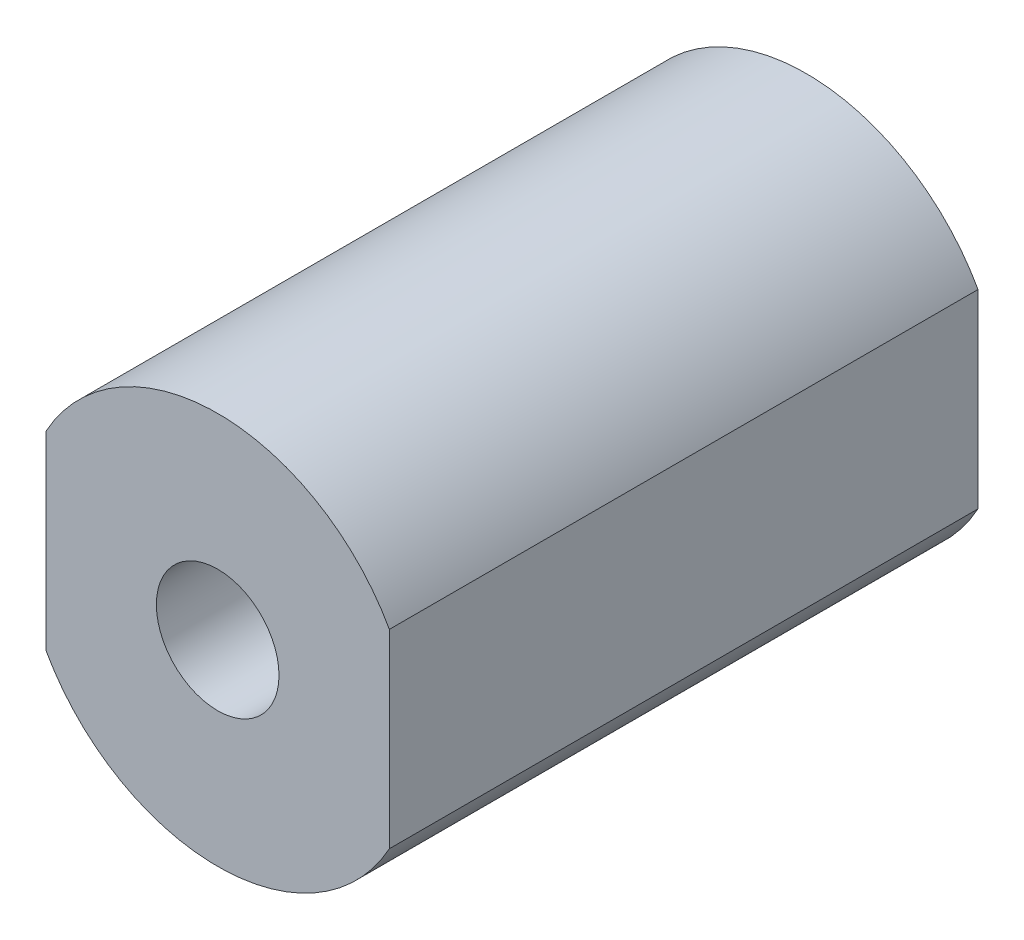
SolidWorks part; units mm, degrees
ref_plane "Front Plane" through (0, 0, 0) normal (0, 0, 1) x (1, 0, 0)
ref_plane "Top Plane" through (0, 0, 0) normal (0, 1, 0) x (1, 0, 0)
ref_plane "Right Plane" through (0, 0, 0) normal (1, 0, 0) x (0, 0, -1)
sketch "Sketch1" plane through (0, 0, 0) normal (0, 0, 1) x (1, 0, 0)
  line L0 (0, 0) -> (0, -4.709) construction
  line L1 (3.5, 1.9365) -> (3.5, -1.9365)
  line L2 (-3.5, 1.9365) -> (-3.5, -1.9365)
  arc A0 (-3.5, -1.9365) -> (3.5, -1.9365) centre (0, 0) ccw
  circle A1 centre (0, 0) radius 1.25
  arc A2 (3.5, 1.9365) -> (-3.5, 1.9365) centre (0, 0) ccw
  dimension "D1" = 8
  dimension "D2" = 2.5
  dimension "D3" = 3.5
extrude "Boss-Extrude1" add sketch "Sketch1" along normal blind 12
sketch "Sketch2" plane through (0, 0, 12) normal (0, 0, 1) x (1, 0, 0)
  circle A0 centre (0, 0) radius 1.75
  dimension "D1" = 3.5
extrude "Cut-Extrude1" [suppressed] cut sketch "Sketch2" against normal blind 6
sketch "Sketch3" plane through (0, 0, 0) normal (0, 0, -1) x (-1, 0, 0)
  circle A0 centre (0, 0) radius 1.25
extrude "Boss-Extrude2" add sketch "Sketch3" against normal blind 0.3
